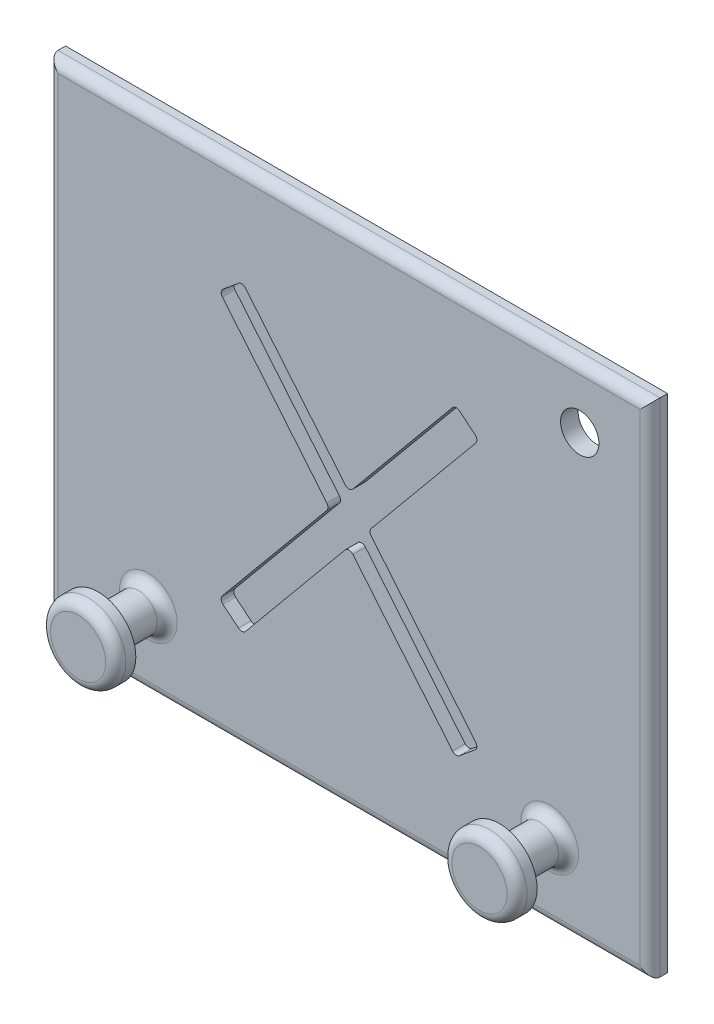
SolidWorks part; units mm, degrees
ref_plane "Front Plane" through (0, 0, 0) normal (0, 0, 1) x (1, 0, 0)
ref_plane "Top Plane" through (0, 0, 0) normal (0, 1, 0) x (1, 0, 0)
ref_plane "Right Plane" through (0, 0, 0) normal (1, 0, 0) x (0, 0, -1)
sketch "Sketch1" plane through (0, 0, 0) normal (0, 0, 1) x (1, 0, 0)
  line L1 (-60, -50) -> (60, -50)
  line L2 (-60, -50) -> (-60, 50)
  line L3 (-60, 50) -> (60, 50)
  line L4 (60, -50) -> (60, 50)
  line L5 (-60, -50) -> (60, 50) construction
  line L6 (-60, 50) -> (60, -50) construction
  point P0 (0, 0)
  dimension "D1" = 120
  dimension "D2" = 100
extrude "Boss-Extrude1" add sketch "Sketch1" along normal blind 3.5
sketch "Sketch9" plane through (0, 0, 3.5) normal (0, 0, 1) x (1, 0, 0)
  line L0 (60, 50) -> (-60, 50) construction
  line L1 (60, -50) -> (60, 50) construction
  circle A0 centre (46, 38) radius 3.825
  dimension "D1" = 7.65
  dimension "D2" = 12
  dimension "D3" = 14
extrude "Cut-Extrude4" cut sketch "Sketch9" against normal blind 4
fillet "Fillet1" radius 2 4 edges at (0, -50, 3.5) (60, 0, 3.5) (0, 50, 3.5) (-60, 0, 3.5)
sketch "Sketch10" plane through (0, 0, 3.5) normal (0, 0, 1) x (1, 0, 0)
  line L0 (60, -50) -> (-60, -50) construction
  line L1 (-60, -50) -> (-60, 50) construction
  line L2 (60, 50) -> (60, -50) construction
  circle A0 centre (-40, -35) radius 3.75
  circle A1 centre (40, -35) radius 3.75
  dimension "D1" = 7.5
  dimension "D2" = 7.5
  dimension "D3" = 15
  dimension "D5" = 15
  dimension "D4" = 20
  dimension "D6" = 20
extrude "Boss-Extrude4" add sketch "Sketch10" along normal blind 10
sketch "Sketch11" plane through (0, 0, 13.5) normal (0, 0, 1) x (1, 0, 0)
  circle A0 centre (-40, -35) radius 7.5
  dimension "D1" = 15
extrude "Boss-Extrude5" add sketch "Sketch11" along normal blind 4
sketch "Sketch12" plane through (0, 0, 13.5) normal (0, 0, 1) x (1, 0, 0)
  circle A0 centre (40, -35) radius 7.5
  dimension "D1" = 15
extrude "Boss-Extrude6" add sketch "Sketch12" along normal blind 4
fillet "Fillet2" radius 2 5 edges at (-43.75, -35, 3.5) (36.25, -35, 3.5) (43.75, -35, 13.5) (47.5, -35, 17.5) (-32.5, -35, 17.5)
sketch "Sketch19" plane through (0, 0, 3.5) normal (0, 0, 1) x (1, 0, 0)
  line L0 (-58, 0) -> (0, -48) construction
  line L1 (-58, 48) -> (-58, -48) construction
  line L2 (-58, -48) -> (58, -48) construction
  line L3 (0, -48) -> (58, 0) construction
  line L4 (58, -48) -> (58, 48) construction
  line L5 (58, 0) -> (0, 48) construction
  line L6 (58, 48) -> (-58, 48) construction
  line L7 (0, 48) -> (-58, 0) construction
  line L8 (-21.2654, -30.4011) -> (-25.8878, -26.5757)
  line L9 (-21.2654, -30.4011) -> (0, -4.7054)
  line L10 (-25.8878, -26.5757) -> (-3.8941, 0)
  line L11 (25.8878, 26.5757) -> (21.2654, 30.4011)
  line L14 (-25.8878, 26.5757) -> (-21.2654, 30.4011)
  line L15 (-25.8878, 26.5757) -> (-3.8941, 0)
  line L16 (-21.2654, 30.4011) -> (0, 4.7054)
  line L17 (21.2654, -30.4011) -> (25.8878, -26.5757)
  line L20 (0, -4.7054) -> (21.2654, -30.4011)
  line L24 (0, 4.7054) -> (21.2654, 30.4011)
  line L25 (3.8941, 0) -> (25.8878, 26.5757)
  line L26 (3.8941, 0) -> (25.8878, -26.5757)
  point P13 (0, 0)
  point P14 (0, 0)
  dimension "D1" = 6
  dimension "D2" = 73.9579
  dimension "D3" = 6
  dimension "D4" = 6
extrude "Cut-Extrude9" cut sketch "Sketch19" against normal blind 2.5
fillet "Fillet3" radius 1 12 edges at (-25.8878, 26.5757, 2.25) (-21.2654, 30.4011, 2.25) (21.2654, 30.4011, 2.25) (25.8878, 26.5757, 2.25) (25.8878, -26.5757, 2.25) (21.2654, -30.4011, 2.25) (-21.2654, -30.4011, 2.25) (-25.8878, -26.5757, 2.25) (-3.8941, 0, 2.25) (0, 4.7054, 2.25) (3.8941, 0, 2.25) (0, -4.7054, 2.25)
